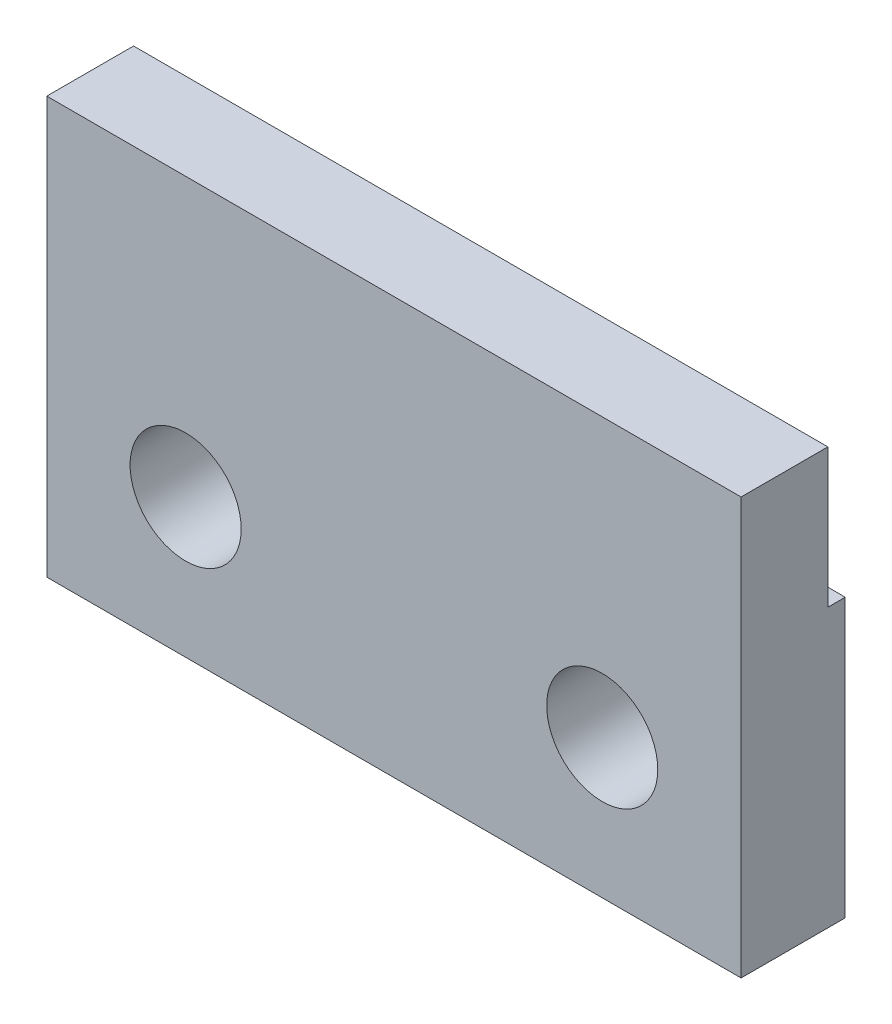
SolidWorks part; units mm, degrees
material "6061-T6 (SS)"
ref_plane "Front Plane" through (0, 0, 0) normal (0, 0, 1) x (1, 0, 0)
ref_plane "Top Plane" through (0, 0, 0) normal (0, 1, 0) x (1, 0, 0)
ref_plane "Right Plane" through (0, 0, 0) normal (1, 0, 0) x (0, 0, -1)
sketch "Sketch1" plane through (0, 0, 0) normal (0, 0, 1) x (1, 0, 0)
  line L0 (6, -2) -> (-6, -2) construction
  line L1 (10, -6) -> (-10, -6)
  line L2 (10, -6) -> (10, 6)
  line L3 (10, 6) -> (-10, 6)
  line L4 (-10, -6) -> (-10, 6)
  line L5 (10, -6) -> (-10, 6) construction
  line L6 (10, 6) -> (-10, -6) construction
  point P0 (0, 0)
  point P6 (0, 0)
  point P9 (0, 0)
  point P10 (0, -2)
  dimension "D1" = 20
  dimension "D2" = 12
  dimension "D3" = 12
  dimension "D4" = 4
extrude "Boss-Extrude1" add sketch "Sketch1" along normal blind 3
sketch "Sketch2" plane through (0, 0, 0) normal (0, 0, -1) x (-1, 0, 0)
  line L0 (10, 6) -> (10, -6) construction
  line L1 (-10, 6) -> (10, 6)
  line L2 (-10, 6) -> (-10, 2)
  line L3 (-10, 2) -> (10, 2)
  line L4 (10, 6) -> (10, 2)
  dimension "D1" = 4
extrude "Cut-Extrude1" cut sketch "Sketch2" against normal blind 0.5
hole_wizard "M3 Clearance Hole1" positions "Sketch3" profile "Sketch4" hole size "M3" standard "ANSI Metric" end condition up to next
sketch "Sketch3" plane through (0, 0, 3) normal (0, 0, 1) x (1, 0, 0)
  point P0 (-6, -2)
  point P3 (6, -2)
sketch "Sketch4" plane through (-6, -2, 3) normal (1, 0, 0) x (0, -1, 0)
  line L0 (0, 0) -> (0, 3)
  line L1 (0, 3) -> (1.6, 3)
  line L2 (1.6, 3) -> (1.6, 0)
  line L5 (1.6, 0) -> (0, 0)
  line L11 (0, -6.35) -> (0, 107.95) construction
  dimension "Thru Hole Dia." = 3.2
  dimension "Thru Hole Depth" = 3
